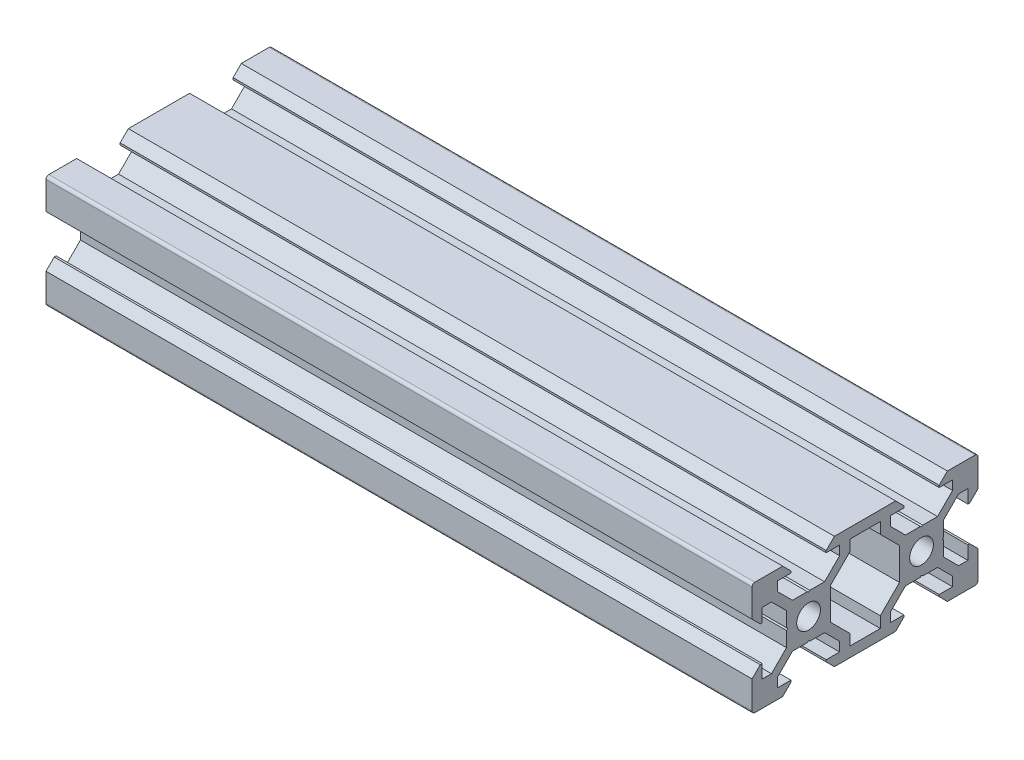
SolidWorks part; units mm, degrees
material "6061-T6 (SS)"
ref_plane "Top" through (0, 0, 0) normal (0, 0, 1) x (1, 0, 0)
ref_plane "Front" through (0, 0, 0) normal (0, 1, 0) x (1, 0, 0)
ref_plane "Right" through (0, 0, 0) normal (1, 0, 0) x (0, 0, -1)
sketch "Profile Sketch" plane through (0, 0, 0) normal (1, 0, 0) x (0, 0, -1)
  line L0 (5.42, 10) -> (-5.42, 10)
  line L1 (-4.5, 8.2) -> (-4.5, 6.56)
  line L2 (-4.5, 6.56) -> (-7.16, 3.9)
  line L3 (-7.16, 3.9) -> (-9.79, 3.9)
  line L4 (-9.79, 3.9) -> (-10, 3.69)
  line L5 (2.7, 8.2) -> (-2.7, 8.2)
  line L6 (-2.7, 8.2) -> (-2.7, 6.2387)
  line L7 (-2.7, 6.2387) -> (-6.1, 2.8387)
  line L8 (-6.1, 2.8387) -> (-6.1, -0.21)
  line L9 (-6.875, 8.545) -> (-6.875, 8.2)
  line L10 (-6.875, 8.2) -> (-4.5, 8.2)
  line L11 (-6.875, 8.545) -> (-5.42, 10)
  line L12 (0, -10) -> (0, 10) construction
  line L13 (-20, 0) -> (20, 0) construction
  line L14 (-10, -10) -> (-10, 10) construction
  line L15 (-6.875, -8.545) -> (-5.42, -10)
  line L16 (-6.875, -8.2) -> (-4.5, -8.2)
  line L17 (-6.875, -8.545) -> (-6.875, -8.2)
  line L18 (-2.7, -6.2387) -> (-6.1, -2.8387)
  line L19 (-2.7, -8.2) -> (-2.7, -6.2387)
  line L20 (2.7, -8.2) -> (-2.7, -8.2)
  line L21 (-7.16, -3.9) -> (-9.79, -3.9)
  line L22 (-4.5, -6.56) -> (-7.16, -3.9)
  line L23 (-4.5, -8.2) -> (-4.5, -6.56)
  line L24 (5.42, -10) -> (-5.42, -10)
  line L25 (-10, 0) -> (-20, 10) construction
  line L26 (-18.545, 3.125) -> (-18.2, 3.125)
  line L27 (-13.125, -8.545) -> (-13.125, -8.2)
  line L28 (-13.125, -8.2) -> (-15.5, -8.2)
  line L29 (-13.125, -8.545) -> (-14.58, -10)
  line L30 (-15.5, -8.2) -> (-15.5, -6.56)
  line L31 (-15.5, -6.56) -> (-12.84, -3.9)
  line L32 (-12.84, -3.9) -> (-10.21, -3.9)
  line L33 (-20, 4.58) -> (-20, 9.5)
  line L34 (-13.9, 2.8387) -> (-13.9, 0.21)
  line L35 (-16.56, 5.5) -> (-13.9, 2.8387)
  line L36 (-12.84, 3.9) -> (-10.21, 3.9)
  line L37 (-15.5, 6.56) -> (-12.84, 3.9)
  line L38 (-15.5, 8.2) -> (-15.5, 6.56)
  line L39 (-13.125, 8.545) -> (-14.58, 10)
  line L40 (-13.125, 8.2) -> (-15.5, 8.2)
  line L41 (-13.125, 8.545) -> (-13.125, 8.2)
  line L42 (-18.2, 3.125) -> (-18.2, 5.5)
  line L43 (-18.545, 3.125) -> (-20, 4.58)
  line L44 (-18.2, 5.5) -> (-16.56, 5.5)
  line L45 (-14.58, 10) -> (-19.5, 10)
  line L46 (-16.56, -5.5) -> (-13.9, -2.8387)
  line L47 (-14.58, -10) -> (-19.5, -10)
  line L48 (-18.2, -5.5) -> (-16.56, -5.5)
  line L49 (-18.545, -3.125) -> (-20, -4.58)
  line L50 (-18.2, -3.125) -> (-18.2, -5.5)
  line L51 (-20, -4.58) -> (-20, -9.5)
  line L52 (-18.545, -3.125) -> (-18.2, -3.125)
  line L53 (10, -10) -> (10, 10) construction
  line L54 (18.545, -3.125) -> (18.2, -3.125)
  line L55 (20, -4.58) -> (20, -9.5)
  line L56 (18.2, -3.125) -> (18.2, -5.5)
  line L57 (18.545, -3.125) -> (20, -4.58)
  line L58 (18.2, -5.5) -> (16.56, -5.5)
  line L59 (14.58, -10) -> (19.5, -10)
  line L60 (16.56, -5.5) -> (13.9, -2.8387)
  line L61 (14.58, 10) -> (19.5, 10)
  line L62 (18.2, 5.5) -> (16.56, 5.5)
  line L63 (18.545, 3.125) -> (20, 4.58)
  line L64 (18.2, 3.125) -> (18.2, 5.5)
  line L65 (13.125, 8.545) -> (13.125, 8.2)
  line L66 (13.125, 8.2) -> (15.5, 8.2)
  line L67 (13.125, 8.545) -> (14.58, 10)
  line L68 (15.5, 8.2) -> (15.5, 6.56)
  line L69 (15.5, 6.56) -> (12.84, 3.9)
  line L70 (12.84, 3.9) -> (10.21, 3.9)
  line L71 (16.56, 5.5) -> (13.9, 2.8387)
  line L72 (13.9, 2.8387) -> (13.9, 0.21)
  line L73 (20, 4.58) -> (20, 9.5)
  line L74 (12.84, -3.9) -> (10.21, -3.9)
  line L75 (15.5, -6.56) -> (12.84, -3.9)
  line L76 (15.5, -8.2) -> (15.5, -6.56)
  line L77 (13.125, -8.545) -> (14.58, -10)
  line L78 (13.125, -8.2) -> (15.5, -8.2)
  line L79 (13.125, -8.545) -> (13.125, -8.2)
  line L80 (18.545, 3.125) -> (18.2, 3.125)
  line L81 (4.5, -8.2) -> (4.5, -6.56)
  line L82 (4.5, -6.56) -> (7.16, -3.9)
  line L83 (7.16, -3.9) -> (9.79, -3.9)
  line L84 (2.7, -8.2) -> (2.7, -6.2387)
  line L85 (2.7, -6.2387) -> (6.1, -2.8387)
  line L86 (6.875, -8.545) -> (6.875, -8.2)
  line L87 (6.875, -8.2) -> (4.5, -8.2)
  line L88 (6.875, -8.545) -> (5.42, -10)
  line L89 (6.875, 8.545) -> (5.42, 10)
  line L90 (6.875, 8.2) -> (4.5, 8.2)
  line L91 (6.875, 8.545) -> (6.875, 8.2)
  line L92 (6.1, 2.8387) -> (6.1, -0.21)
  line L93 (2.7, 6.2387) -> (6.1, 2.8387)
  line L94 (2.7, 8.2) -> (2.7, 6.2387)
  line L95 (9.79, 3.9) -> (10, 3.69)
  line L96 (7.16, 3.9) -> (9.79, 3.9)
  line L97 (4.5, 6.56) -> (7.16, 3.9)
  line L98 (4.5, 8.2) -> (4.5, 6.56)
  line L99 (-10, 3.69) -> (-10.21, 3.9)
  line L100 (-10, -3.69) -> (-10.21, -3.9)
  line L101 (-9.79, -3.9) -> (-10, -3.69)
  line L102 (-13.9, -0.21) -> (-13.69, 0)
  line L103 (-13.69, 0) -> (-13.9, 0.21)
  line L104 (-13.9, -0.21) -> (-13.9, -2.8387)
  line L105 (-6.1, -0.21) -> (-6.31, 0)
  line L106 (-6.31, 0) -> (-6.1, -0.21)
  line L107 (-6.1, -0.21) -> (-6.1, -2.8387)
  line L108 (6.31, 0) -> (6.1, -0.21)
  line L109 (6.1, -0.21) -> (6.31, 0)
  line L110 (13.69, 0) -> (13.9, 0.21)
  line L111 (13.9, -0.21) -> (13.69, 0)
  line L112 (9.79, -3.9) -> (10, -3.69)
  line L113 (10, -3.69) -> (10.21, -3.9)
  line L114 (10, 3.69) -> (10.21, 3.9)
  line L115 (6.1, -0.21) -> (6.1, -2.8387)
  line L116 (13.9, -0.21) -> (13.9, -2.8387)
  line L118 (20, -10) -> (20, 10) construction
  line L119 (20, -10) -> (-20, -10) construction
  line L120 (-20, -10) -> (-20, 10) construction
  line L121 (20, 10) -> (-20, 10) construction
  line L122 (20, -10) -> (-20, 10) construction
  line L123 (-20, -10) -> (20, 10) construction
  circle A0 centre (-10, 0) radius 2.1
  arc A1 (-19.5, 10) -> (-20, 9.5) centre (-19.5, 9.5) ccw
  arc A2 (-19.5, -10) -> (-20, -9.5) centre (-19.5, -9.5) cw
  arc A3 (19.5, -10) -> (20, -9.5) centre (19.5, -9.5) ccw
  arc A4 (19.5, 10) -> (20, 9.5) centre (19.5, 9.5) cw
  circle A5 centre (10, 0) radius 2.1
  point P35 (-2.4957, 0)
  point P108 (0, -8.2)
  point P119 (0, 8.2)
  point P123 (2.4957, 0)
  point P131 (0, 0)
  point P143 (0, 0)
  dimension "D4" = 5.42
  dimension "D5" = 40
  dimension "D6" = 4.2
  dimension "D16" = 0.5
  dimension "D1" = 0.21
  dimension "D2" = 45
  dimension "D3" = 20
  dimension "D7" = 1.5
  dimension "D8" = 1.8
  dimension "D9" = 10
  dimension "D10" = 3.9
  dimension "D11" = 3.9
  dimension "D12" = 1.8
  dimension "D13" = 3.125
  dimension "D14" = 5.5
  dimension "D15" = 1.64
  dimension "D17" = 5.4
extrude "Profile Extrude" add sketch "Profile Sketch" along normal blind 125 contours A4 L61 L67 L65 L66 L68 L69 L70 L114 L95 L96 L97 L98 L90 L91 L89 L0 L11 L9 L10 L1 L2 L3 L4 L99 L36 L37 L38 L40 L41 L39 L45 A1 L33 L43 L26 L42 L44 L35 L34 L103 L102 L104 L46 L48 L50 L52 L49 L51 A2 L47
equation "\"M2x0.4_Tap_Hole_75\"= 1.6"
